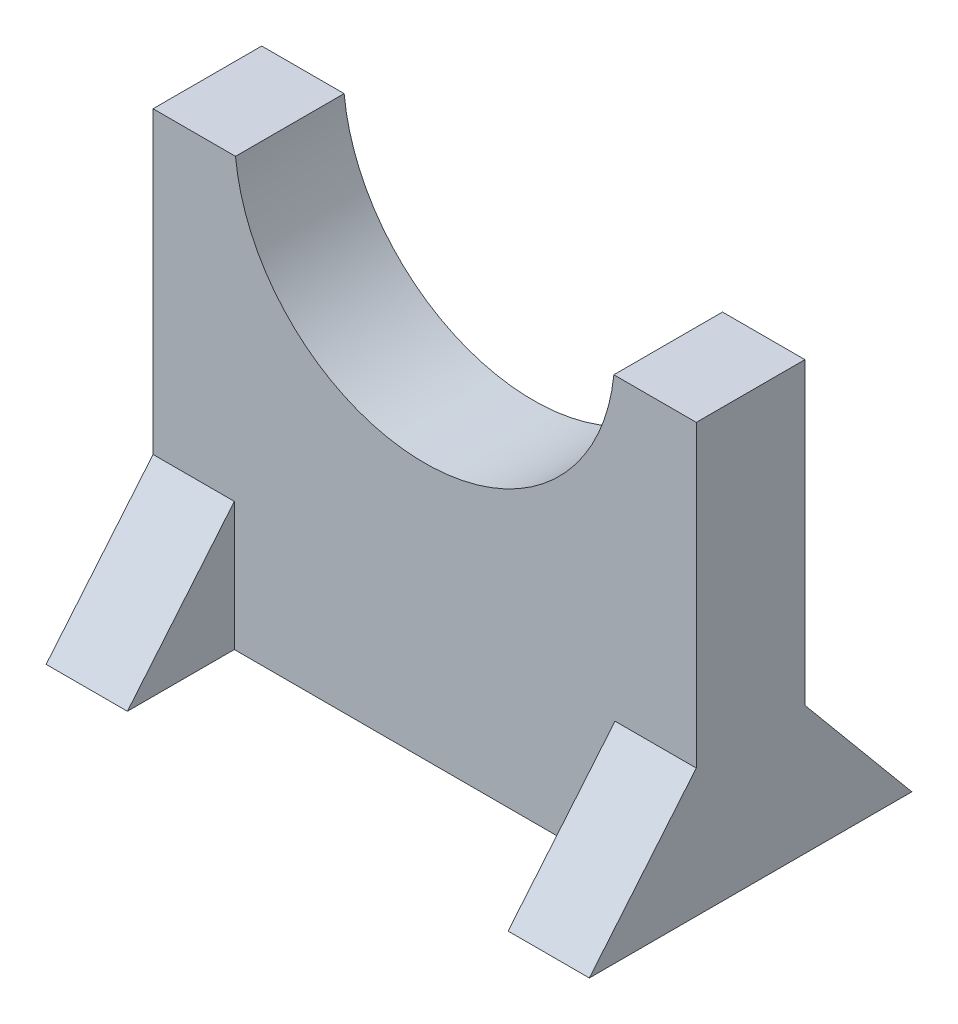
SolidWorks part; units mm, degrees
ref_plane "Front Plane" through (0, 0, 0) normal (0, 0, 1) x (1, 0, 0)
ref_plane "Top Plane" through (0, 0, 0) normal (0, 1, 0) x (1, 0, 0)
ref_plane "Right Plane" through (0, 0, 0) normal (1, 0, 0) x (0, 0, -1)
sketch "Sketch1" plane through (0, 0, 0) normal (0, 1, 0) x (1, 0, 0)
  line L1 (-63.5, 12.7) -> (63.5, 12.7)
  line L2 (-63.5, 12.7) -> (-63.5, -12.7)
  line L3 (-63.5, -12.7) -> (63.5, -12.7)
  line L4 (63.5, 12.7) -> (63.5, -12.7)
  line L5 (-63.5, 12.7) -> (63.5, -12.7) construction
  line L6 (-63.5, -12.7) -> (63.5, 12.7) construction
  point P0 (0, 0)
  dimension "D1" = 25.4
  dimension "D2" = 127
extrude "Boss-Extrude1" add sketch "Sketch1" along normal blind 100
sketch "Sketch2" plane through (0, 0, 12.7) normal (0, 0, 1) x (1, 0, 0)
  line L0 (0, 0) -> (0, 60) construction
  line L1 (0, 60) -> (0, 148.9) construction
  circle A0 centre (0, 104.45) radius 44.45
  dimension "D1" = 60
  dimension "D2" = 88.9
extrude "Cut-Extrude1" cut sketch "Sketch2" against normal blind 30
sketch "Sketch3" plane through (0, 0, 0) normal (0, 1, 0) x (1, 0, 0)
  line L1 (-63.5, 12.7) -> (-44.5, 12.7)
  line L2 (-63.5, 12.7) -> (-63.5, 37.7)
  line L3 (-63.5, 37.7) -> (-44.5, 37.7)
  line L4 (-44.5, 12.7) -> (-44.5, 37.7)
  line L5 (63.5, 12.7) -> (44.5, 12.7)
  line L6 (63.5, 12.7) -> (63.5, 37.7)
  line L7 (63.5, 37.7) -> (44.5, 37.7)
  line L8 (44.5, 12.7) -> (44.5, 37.7)
  line L9 (63.5, -12.7) -> (44.5, -12.7)
  line L10 (63.5, -12.7) -> (63.5, -37.7)
  line L11 (63.5, -37.7) -> (44.5, -37.7)
  line L12 (44.5, -12.7) -> (44.5, -37.7)
  line L13 (-63.5, -12.7) -> (-44.5, -12.7)
  line L14 (-63.5, -12.7) -> (-63.5, -37.7)
  line L15 (-63.5, -37.7) -> (-44.5, -37.7)
  line L16 (-44.5, -12.7) -> (-44.5, -37.7)
  dimension "D1" = 19
  dimension "D2" = 19
  dimension "D3" = 19
  dimension "D4" = 19
  dimension "D5" = 25
  dimension "D6" = 25
  dimension "D7" = 25
  dimension "D8" = 25
extrude "Boss-Extrude2" add sketch "Sketch3" along normal blind 30
sketch "Sketch4" plane through (-63.5, 0, 0) normal (-1, 0, 0) x (0, 0, 1)
  line L0 (12.7, 30) -> (37.7, 0)
  line L1 (37.7, 0) -> (37.7, 30)
  line L2 (37.7, 30) -> (12.7, 30)
  line L3 (-12.7, 30) -> (-37.7, 0)
  line L4 (-37.7, 0) -> (-37.7, 30)
  line L5 (-37.7, 30) -> (-12.7, 30)
extrude "Cut-Extrude2" cut sketch "Sketch4" against normal blind 140
